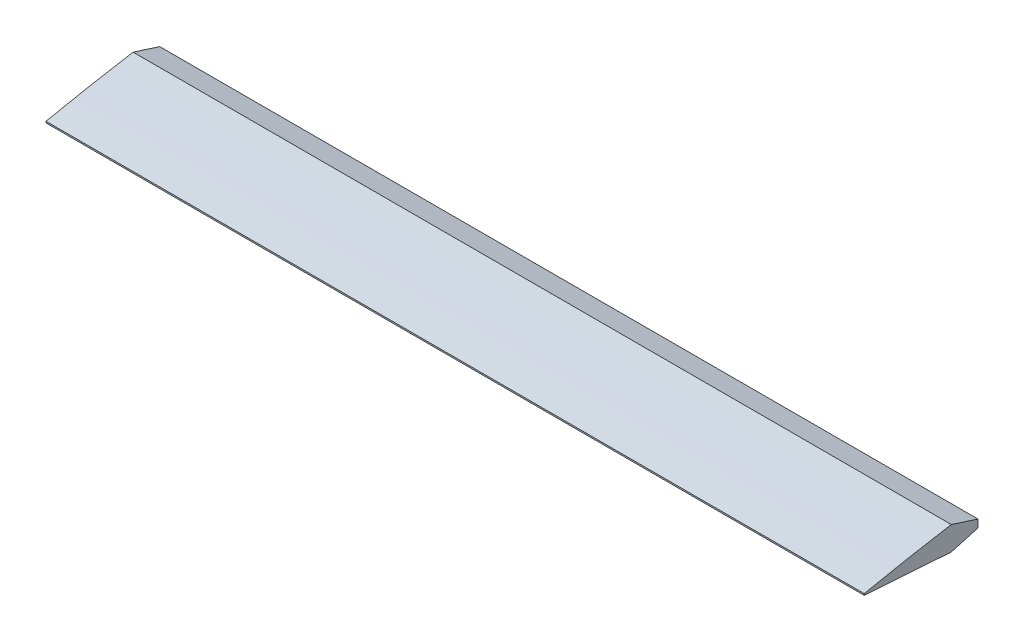
SolidWorks part; units mm, degrees
ref_plane "Front Plane" through (0, 0, 0) normal (0, 0, 1) x (1, 0, 0)
ref_plane "Top Plane" through (0, 0, 0) normal (0, 1, 0) x (1, 0, 0)
ref_plane "Right Plane" through (0, 0, 0) normal (1, 0, 0) x (0, 0, -1)
sketch "Sketch4" plane through (0, 0, 0) normal (0, 0, 1) x (1, 0, 0)
  line L0 (-30.3109, 17.5) -> (30.3109, 17.5)
  arc A1 (30.3109, 17.5) -> (-30.3109, 17.5) centre (0, 0) ccw
  dimension "D1" = 35
  dimension "D2" = 17.5
extrude "Exterior" add sketch "Sketch4" along normal blind 89 contours L0 A1
sketch "Sketch5" plane through (0, 0, 0) normal (0, 0, -1) x (-1, 0, 0)
  line L0 (30.3109, 17.5) -> (-30.3109, 17.5) construction
  line L1 (23.1247, 17.5) -> (-23.1247, 17.5)
  arc A0 (23.1247, 17.5) -> (-23.1247, 17.5) centre (0, 0) ccw
  dimension "D1" = 58
extrude "Boss-Extrude1" add sketch "Sketch5" along normal blind 15
curve "Curve3"
  spline degree 3 poles (0, 1.3, 1000) (0, 4.7133, 983.3426) (0, 11.531, 950.0715) (0, 24.0186, 883.4722) (0, 37.8548, 800.1781) (0, 52.175, 700.1592) (0, 64.1175, 600.1567) (0, 72.8619, 500.1109) (0, 78.7837, 400.0878) (0, 79.786, 316.6355) (0, 77.0249, 249.9395) (0, 72.979, 199.8766) (0, 66.5721, 149.7505) (0, 58.6825, 108.0331) (0, 49.7566, 74.7751) (0, 41.6416, 49.5609) (0, 32.1864, 28.1982) (0, 20.723, 9.771) (0, 0.8988, -6.2982) (0, -16.5264, 10.3934) (0, -24.4739, 28.476) (0, -30.5108, 49.7447) (0, -34.8393, 74.8759) (0, -38.5332, 108.2669) (0, -41.3764, 149.947) (0, -42.5163, 199.9941) (0, -42.3574, 250.0055) (0, -40.8857, 316.6783) (0, -38.2375, 400.0272) (0, -33.6287, 500.0334) (0, -27.6385, 600.0106) (0, -21.4122, 700.0048) (0, -15.1098, 800.0161) (0, -9.3053, 883.3314) (0, -4.8282, 950.0042) (0, -2.4761, 983.334) (0, -1.3, 1000) knots 0 0 0 0 0.025012 0.049959 0.099673 0.149206 0.198581 0.247805 0.296917 0.345953 0.370492 0.395091 0.419815 0.444799 0.45749 0.470406 0.483879 0.491264 0.503459 0.513609 0.520451 0.533235 0.545691 0.558032 0.582609 0.607135 0.631652 0.656174 0.705234 0.75432 0.803437 0.852566 0.901701 0.950849 0.975423 1 1 1 1
sketch "Sketch7" plane through (0, 0, 0) normal (1, 0, 0) x (0, 0, -1)
  line L0 (-89, 21.3887) -> (-89, 21.1573)
  line L1 (-89, 21.273) -> (0, 21.3903) construction
  line L2 (0, 21.3903) -> (-0.0573, 64.8516) construction
  line L7 (-89, 17.5) -> (0, 17.5) construction
  line L9 (0, 17.5) -> (0, 29) construction
  spline S1 degree 3 poles (-89, 21.3887) (-87.5176, 21.6924) (-84.5567, 22.2992) (-78.6297, 23.4105) (-71.2171, 24.6418) (-62.316, 25.9162) (-53.4164, 26.979) (-44.5129, 27.7573) (-35.6114, 28.2842) (-28.1847, 28.3735) (-22.2492, 28.1277) (-17.7939, 27.7677) (-13.3329, 27.1975) (-9.6203, 26.4954) (-6.6606, 25.701) (-4.4167, 24.9788) (-2.5155, 24.1374) (-0.8756, 23.1172) (0.5545, 21.353) (-0.931, 19.8022) (-2.5402, 19.095) (-4.433, 18.5577) (-6.6696, 18.1725) (-9.6412, 17.8438) (-13.3504, 17.5907) (-17.8043, 17.4893) (-22.255, 17.5034) (-28.1885, 17.6344) (-35.606, 17.8701) (-44.506, 18.2802) (-53.4034, 18.8133) (-62.3022, 19.3674) (-71.2026, 19.9283) (-78.6172, 20.4449) (-84.5507, 20.8433) (-87.5168, 21.0526) (-89, 21.1573) knots 0 0 0 0 0.025012 0.049959 0.099673 0.149206 0.198581 0.247805 0.296917 0.345953 0.370492 0.395091 0.419815 0.444799 0.45749 0.470406 0.483879 0.491264 0.503459 0.513609 0.520451 0.533235 0.545691 0.558032 0.582609 0.607135 0.631652 0.656174 0.705234 0.75432 0.803437 0.852566 0.901701 0.950849 0.975423 1 1 1 1
  dimension "D1" = 89
ref_plane "Plane1" through (80, 0, 0) normal (1, 0, 0) x (0, 0, -1)
ref_plane "Plane2" through (-80, 0, 0) normal (1, 0, 0) x (0, 0, -1)
sketch "Sketch8" plane through (80, 0, 0) normal (1, 0, 0) x (0, 0, -1)
  line L0 (-89, 21.3887) -> (-89, 21.1573)
  spline S0 degree 3 poles (-469.3669, 946.2185) (-209.3584, -26.81) (-147.9272, 10.417) (-78.6297, 23.4105) (-71.2171, 24.6418) (-62.316, 25.9162) (-53.4164, 26.979) (-44.5129, 27.7573) (-35.6114, 28.2842) (-28.1847, 28.3735) (-22.2492, 28.1277) (-17.7939, 27.7677) (-13.3329, 27.1975) (-9.6203, 26.4954) (-6.6606, 25.701) (-4.4167, 24.9788) (-2.5155, 24.1374) (-0.8756, 23.1172) (0.5545, 21.353) (-0.931, 19.8022) (-2.5402, 19.095) (-4.433, 18.5577) (-6.6696, 18.1725) (-9.6412, 17.8438) (-13.3504, 17.5907) (-17.8043, 17.4893) (-22.255, 17.5034) (-28.1885, 17.6344) (-35.606, 17.8701) (-44.506, 18.2802) (-53.4034, 18.8133) (-62.3022, 19.3674) (-71.2026, 19.9283) (-78.6172, 20.4449) (-191.4759, 28.0234) (-300.415, 49.2551) (-474.7288, -901.4445) knots -1.065698 -1.065698 -1.065698 -1.065698 0.025012 0.049959 0.099673 0.149206 0.198581 0.247805 0.296917 0.345953 0.370492 0.395091 0.419815 0.444799 0.45749 0.470406 0.483879 0.491264 0.503459 0.513609 0.520451 0.533235 0.545691 0.558032 0.582609 0.607135 0.631652 0.656174 0.705234 0.75432 0.803437 0.852566 0.901701 0.950849 0.975423 2.771414 2.771414 2.771414 2.771414 only from (-89, 21.3887) to (-89, 21.1573) construction
  spline S1 degree 3 poles (-89, 21.3887) (-87.5176, 21.6924) (-84.5567, 22.2992) (-78.6297, 23.4105) (-71.2171, 24.6418) (-62.316, 25.9162) (-53.4164, 26.979) (-44.5129, 27.7573) (-35.6114, 28.2842) (-28.1847, 28.3735) (-22.2492, 28.1277) (-17.7939, 27.7677) (-13.3329, 27.1975) (-9.6203, 26.4954) (-6.6606, 25.701) (-4.4167, 24.9788) (-2.5155, 24.1374) (-0.8756, 23.1172) (0.5545, 21.353) (-0.931, 19.8022) (-2.5402, 19.095) (-4.433, 18.5577) (-6.6696, 18.1725) (-9.6412, 17.8438) (-13.3504, 17.5907) (-17.8043, 17.4893) (-22.255, 17.5034) (-28.1885, 17.6344) (-35.606, 17.8701) (-44.506, 18.2802) (-53.4034, 18.8133) (-62.3022, 19.3674) (-71.2026, 19.9283) (-78.6172, 20.4449) (-84.5507, 20.8433) (-87.5168, 21.0526) (-89, 21.1573) knots 0 0 0 0 0.025012 0.049959 0.099673 0.149206 0.198581 0.247805 0.296917 0.345953 0.370492 0.395091 0.419815 0.444799 0.45749 0.470406 0.483879 0.491264 0.503459 0.513609 0.520451 0.533235 0.545691 0.558032 0.582609 0.607135 0.631652 0.656174 0.705234 0.75432 0.803437 0.852566 0.901701 0.950849 0.975423 1 1 1 1
sketch "Sketch9" plane through (-80, 0, 0) normal (1, 0, 0) x (0, 0, -1)
  line L0 (-89, 21.3887) -> (-89, 21.1573)
  spline S0 degree 3 poles (-469.3669, 946.2185) (-209.3584, -26.81) (-147.9272, 10.417) (-78.6297, 23.4105) (-71.2171, 24.6418) (-62.316, 25.9162) (-53.4164, 26.979) (-44.5129, 27.7573) (-35.6114, 28.2842) (-28.1847, 28.3735) (-22.2492, 28.1277) (-17.7939, 27.7677) (-13.3329, 27.1975) (-9.6203, 26.4954) (-6.6606, 25.701) (-4.4167, 24.9788) (-2.5155, 24.1374) (-0.8756, 23.1172) (0.5545, 21.353) (-0.931, 19.8022) (-2.5402, 19.095) (-4.433, 18.5577) (-6.6696, 18.1725) (-9.6412, 17.8438) (-13.3504, 17.5907) (-17.8043, 17.4893) (-22.255, 17.5034) (-28.1885, 17.6344) (-35.606, 17.8701) (-44.506, 18.2802) (-53.4034, 18.8133) (-62.3022, 19.3674) (-71.2026, 19.9283) (-78.6172, 20.4449) (-191.4759, 28.0234) (-300.415, 49.2551) (-474.7288, -901.4445) knots -1.065698 -1.065698 -1.065698 -1.065698 0.025012 0.049959 0.099673 0.149206 0.198581 0.247805 0.296917 0.345953 0.370492 0.395091 0.419815 0.444799 0.45749 0.470406 0.483879 0.491264 0.503459 0.513609 0.520451 0.533235 0.545691 0.558032 0.582609 0.607135 0.631652 0.656174 0.705234 0.75432 0.803437 0.852566 0.901701 0.950849 0.975423 2.771414 2.771414 2.771414 2.771414 only from (-89, 21.3887) to (-89, 21.1573) construction
  spline S1 degree 3 poles (-89, 21.3887) (-87.5176, 21.6924) (-84.5567, 22.2992) (-78.6297, 23.4105) (-71.2171, 24.6418) (-62.316, 25.9162) (-53.4164, 26.979) (-44.5129, 27.7573) (-35.6114, 28.2842) (-28.1847, 28.3735) (-22.2492, 28.1277) (-17.7939, 27.7677) (-13.3329, 27.1975) (-9.6203, 26.4954) (-6.6606, 25.701) (-4.4167, 24.9788) (-2.5155, 24.1374) (-0.8756, 23.1172) (0.5545, 21.353) (-0.931, 19.8022) (-2.5402, 19.095) (-4.433, 18.5577) (-6.6696, 18.1725) (-9.6412, 17.8438) (-13.3504, 17.5907) (-17.8043, 17.4893) (-22.255, 17.5034) (-28.1885, 17.6344) (-35.606, 17.8701) (-44.506, 18.2802) (-53.4034, 18.8133) (-62.3022, 19.3674) (-71.2026, 19.9283) (-78.6172, 20.4449) (-84.5507, 20.8433) (-87.5168, 21.0526) (-89, 21.1573) knots 0 0 0 0 0.025012 0.049959 0.099673 0.149206 0.198581 0.247805 0.296917 0.345953 0.370492 0.395091 0.419815 0.444799 0.45749 0.470406 0.483879 0.491264 0.503459 0.513609 0.520451 0.533235 0.545691 0.558032 0.582609 0.607135 0.631652 0.656174 0.705234 0.75432 0.803437 0.852566 0.901701 0.950849 0.975423 1 1 1 1
loft "Loft9" add profiles "Sketch8", "Sketch9"
sketch "Sketch12" plane through (80, 0, 0) normal (1, 0, 0) x (0, 0, -1)
  line L0 (-89, 21.3887) -> (-89, 21.1573) construction
  line L1 (-89, 21.3887) -> (-89, 21.1573)
  line L2 (-89, 21.3887) -> (-97.2409, 26.9065)
  line L3 (-97.2409, 26.9065) -> (-90.2923, 42.7722)
  line L4 (-90.2923, 42.7722) -> (-30.1138, 44.0233)
  line L5 (-30.1138, 44.0233) -> (6.4186, 38.5184)
  line L6 (6.4186, 38.5184) -> (-0.0099, 28.9175)
  line L7 (0, 21.3903) -> (-0.0573, 64.8516) construction
  line L8 (-0.0099, 28.9175) -> (-30.6202, 28.3197)
  spline S0 degree 3 poles (-713.3875, 1915.884) (-239.966, -47.1163) (-164.6221, 7.2867) (-78.6297, 23.4105) (-71.2171, 24.6418) (-62.316, 25.9162) (-53.4164, 26.979) (-44.5129, 27.7573) (-35.6114, 28.2842) (-28.1847, 28.3735) (-22.2492, 28.1277) (-17.7939, 27.7677) (-13.3329, 27.1975) (-9.6203, 26.4954) (-6.6606, 25.701) (-4.4167, 24.9788) (-2.5155, 24.1374) (-0.8756, 23.1172) (0.5545, 21.353) (-0.931, 19.8022) (-2.5402, 19.095) (-4.433, 18.5577) (-6.6696, 18.1725) (-9.6412, 17.8438) (-13.3504, 17.5907) (-17.8043, 17.4893) (-22.255, 17.5034) (-28.1885, 17.6344) (-35.606, 17.8701) (-44.506, 18.2802) (-53.4034, 18.8133) (-62.3022, 19.3674) (-71.2026, 19.9283) (-78.6172, 20.4449) (-220.4152, 29.9667) (-357.7257, 61.3982) (-629.9057, -1889.2617) knots -1.346455 -1.346455 -1.346455 -1.346455 0.025012 0.049959 0.099673 0.149206 0.198581 0.247805 0.296917 0.345953 0.370492 0.395091 0.419815 0.444799 0.45749 0.470406 0.483879 0.491264 0.503459 0.513609 0.520451 0.533235 0.545691 0.558032 0.582609 0.607135 0.631652 0.656174 0.705234 0.75432 0.803437 0.852566 0.901701 0.950849 0.975423 3.250848 3.250848 3.250848 3.250848 only from (-89, 21.3887) to (-89, 21.1573) construction
  spline S1 degree 3 poles (-89, 21.3887) (-87.5176, 21.6924) (-84.5567, 22.2992) (-78.6297, 23.4105) (-71.2171, 24.6418) (-62.316, 25.9162) (-53.4164, 26.979) (-44.5129, 27.7573) (-36.9147, 28.2071) (-32.2817, 28.3107) (-30.6202, 28.3197) knots 0 0 0 0 0.025012 0.049959 0.099673 0.149206 0.198581 0.247805 0.296917 0.324377 0.324377 0.324377 0.324377
  spline S2 degree 3 poles (-89, 21.3887) (-87.5176, 21.6924) (-84.5567, 22.2992) (-78.6297, 23.4105) (-71.2171, 24.6418) (-62.316, 25.9162) (-53.4164, 26.979) (-44.5129, 27.7573) (-36.9147, 28.2071) (-32.2817, 28.3107) (-30.6202, 28.3197) knots 0 0 0 0 0.025012 0.049959 0.099673 0.149206 0.198581 0.247805 0.296917 0.324377 0.324377 0.324377 0.324377
extrude "Cut-Extrude1" cut sketch "Sketch12" against normal through all
ref_plane "Plane3" through (0, 30, 0) normal (0, 1, 0) x (1, 0, 0)
sketch "Sketch17" plane through (-80, 0, 0) normal (-1, 0, 0) x (0, 0, 1)
  line L0 (89, 21.3887) -> (89, 21.1573) construction
  line L1 (89, 21.3887) -> (89, 21.1573)
  spline S0 degree 3 poles (713.3875, 1915.884) (239.966, -47.1163) (164.6221, 7.2867) (78.6297, 23.4105) (71.2171, 24.6418) (62.316, 25.9162) (53.4164, 26.979) (44.5129, 27.7573) (35.6114, 28.2842) (28.1847, 28.3735) (22.2492, 28.1277) (17.7939, 27.7677) (13.3329, 27.1975) (9.6203, 26.4954) (6.6606, 25.701) (4.4167, 24.9788) (2.5155, 24.1374) (0.8756, 23.1172) (-0.5545, 21.353) (0.931, 19.8022) (2.5402, 19.095) (4.433, 18.5577) (6.6696, 18.1725) (9.6412, 17.8438) (13.3504, 17.5907) (17.8043, 17.4893) (22.255, 17.5034) (28.1885, 17.6344) (35.606, 17.8701) (44.506, 18.2802) (53.4034, 18.8133) (62.3022, 19.3674) (71.2026, 19.9283) (78.6172, 20.4449) (220.4152, 29.9667) (357.7257, 61.3982) (629.9057, -1889.2617) knots -1.346455 -1.346455 -1.346455 -1.346455 0.025012 0.049959 0.099673 0.149206 0.198581 0.247805 0.296917 0.345953 0.370492 0.395091 0.419815 0.444799 0.45749 0.470406 0.483879 0.491264 0.503459 0.513609 0.520451 0.533235 0.545691 0.558032 0.582609 0.607135 0.631652 0.656174 0.705234 0.75432 0.803437 0.852566 0.901701 0.950849 0.975423 3.250848 3.250848 3.250848 3.250848 only from (89, 21.3887) to (89, 21.1573) construction
  spline S1 degree 3 poles (89, 21.3887) (87.5176, 21.6924) (84.5567, 22.2992) (78.6297, 23.4105) (71.2171, 24.6418) (62.316, 25.9162) (53.4164, 26.979) (44.5129, 27.7573) (35.6114, 28.2842) (28.1847, 28.3735) (22.2492, 28.1277) (17.7939, 27.7677) (13.3329, 27.1975) (9.6203, 26.4954) (6.6606, 25.701) (4.4167, 24.9788) (2.5155, 24.1374) (0.8756, 23.1172) (-0.5545, 21.353) (0.931, 19.8022) (2.5402, 19.095) (4.433, 18.5577) (6.6696, 18.1725) (9.6412, 17.8438) (13.3504, 17.5907) (17.8043, 17.4893) (22.255, 17.5034) (28.1885, 17.6344) (35.606, 17.8701) (44.506, 18.2802) (53.4034, 18.8133) (62.3022, 19.3674) (71.2026, 19.9283) (78.6172, 20.4449) (84.5507, 20.8433) (87.5168, 21.0526) (89, 21.1573) knots 0 0 0 0 0.025012 0.049959 0.099673 0.149206 0.198581 0.247805 0.296917 0.345953 0.370492 0.395091 0.419815 0.444799 0.45749 0.470406 0.483879 0.491264 0.503459 0.513609 0.520451 0.533235 0.545691 0.558032 0.582609 0.607135 0.631652 0.656174 0.705234 0.75432 0.803437 0.852566 0.901701 0.950849 0.975423 1 1 1 1
extrude "Boss-Extrude2" add sketch "Sketch17" along normal blind 170
ref_plane "Plane5" through (-165, 0, 0) normal (1, 0, 0) x (0, 0, -1)
ref_plane "Plane6" through (-80, 0, 0) normal (1, 0, 0) x (0, 0, -1)
sketch "Sketch18" plane through (-80, 0, 0) normal (1, 0, 0) x (0, 0, -1)
  line L0 (-99.867, 5.7154) -> (-104.3901, 63.3258)
  line L1 (-104.3901, 63.3258) -> (31.8989, 60.8261)
  line L2 (31.8989, 60.8261) -> (39.2788, -3.2119)
  line L3 (39.2788, -3.2119) -> (-99.867, 5.7154)
extrude "Cut-Extrude6" cut sketch "Sketch18" along normal through all
sketch "Sketch13" plane through (-80, 0, 0) normal (-1, 0, 0) x (0, 0, 1)
  line L0 (20, 17.5005) -> (20, 27.9379) construction
  circle A0 centre (20, 22.7192) radius 3.25
  spline S0 degree 3 poles (89, 21.3887) (87.5176, 21.6924) (84.5567, 22.2992) (78.6297, 23.4105) (71.2171, 24.6418) (62.316, 25.9162) (53.4164, 26.979) (44.5129, 27.7573) (35.6114, 28.2842) (28.1847, 28.3735) (22.2492, 28.1277) (17.7939, 27.7677) (13.3329, 27.1975) (9.6203, 26.4954) (6.6606, 25.701) (4.4167, 24.9788) (2.5155, 24.1374) (0.8756, 23.1172) (-0.5545, 21.353) (0.931, 19.8022) (2.5402, 19.095) (4.433, 18.5577) (6.6696, 18.1725) (9.6412, 17.8438) (13.3504, 17.5907) (17.8043, 17.4893) (22.255, 17.5034) (28.1885, 17.6344) (35.606, 17.8701) (44.506, 18.2802) (53.4034, 18.8133) (62.3022, 19.3674) (71.2026, 19.9283) (78.6172, 20.4449) (84.5507, 20.8433) (87.5168, 21.0526) (89, 21.1573) knots 0 0 0 0 0.025012 0.049959 0.099673 0.149206 0.198581 0.247805 0.296917 0.345953 0.370492 0.395091 0.419815 0.444799 0.45749 0.470406 0.483879 0.491264 0.503459 0.513609 0.520451 0.533235 0.545691 0.558032 0.582609 0.607135 0.631652 0.656174 0.705234 0.75432 0.803437 0.852566 0.901701 0.950849 0.975423 1 1 1 1 construction
  point P8 (20, 22.7192)
  dimension "D1" = 6.5
  dimension "D2" = 20
extrude "Cut-Extrude2" cut sketch "Sketch13" against normal through all and the other way through all
sketch "Sketch19" plane through (0, 0, 0) normal (0, 1, 0) x (1, 0, 0)
  line L0 (-183.5, -62.5) -> (-183.5, -26.5)
  line L1 (-183.5, -26.5) -> (-146.5, -26.5)
  line L2 (-146.5, -26.5) -> (-146.5, -62.5)
  line L3 (-146.5, -62.5) -> (-183.5, -62.5)
  line L4 (-165, -9.0116) -> (-165, 9.0116) construction
  line L6 (-80, 0) -> (-250, 0) construction
  point P6 (-165, -62.5)
  point P7 (-183.5, -44.5)
  dimension "D1" = 36
  dimension "D2" = 37
  dimension "D3" = 44.5
extrude "Cut-Extrude7" cut sketch "Sketch19" along normal blind 23
sketch "Sketch20" plane through (0, 30, 0) normal (0, 1, 0) x (1, 0, 0)
  line L0 (-229, -89) -> (-229, -71.2)
  line L1 (-229, -71.2) -> (-101, -71.2)
  line L2 (-101, -71.2) -> (-101, -89)
  line L3 (-250, -89) -> (-80, -89) construction
  line L5 (-250, 0) -> (-250, -89) construction
  line L6 (-80, -89) -> (-80, 0) construction
  line L7 (-229, -89) -> (-250, -89)
  line L8 (-250, -89) -> (-250, 0)
  line L9 (-250, 0) -> (-80, 0)
  line L10 (-80, 0) -> (-80, -89)
  line L11 (-80, -89) -> (-101, -89)
  dimension "D1" = 21
  dimension "D2" = 21
extrude "Cut-Extrude8" cut sketch "Sketch20" against normal through all
sketch "Sketch21" plane through (-229, 0, 0) normal (-1, 0, 0) x (0, 0, 1)
  line L0 (71.2, 21.3931) -> (75.3752, 20.22)
  line L1 (71.2, 19.938) -> (71.2, 24.6104) construction
  line L2 (71.2, 22.5975) -> (75.3752, 23.9416)
  line L7 (75.3752, 20.22) -> (73.9843, 18.5521)
  line L8 (73.9843, 18.5521) -> (70.1577, 19.386)
  line L9 (70.1577, 19.386) -> (71.2, 21.3931)
  line L10 (71.2, 22.5975) -> (69.8099, 24.5575)
  line L11 (69.8099, 24.5575) -> (72.8492, 25.7476)
  line L12 (72.8492, 25.7476) -> (75.3752, 23.9416)
  spline S0 degree 3 poles (89, 21.1573) (87.5168, 21.0526) (84.5507, 20.8433) (78.6168, 20.4448) (74.1672, 20.1348) (71.2, 19.938) knots 0.901694 0.901694 0.901694 0.901694 0.926272 0.950845 1 1 1 1 construction
  spline S1 degree 3 poles (71.2, 24.6104) (74.1727, 24.1509) (78.6293, 23.4106) (84.5567, 22.2992) (87.5176, 21.6924) (89, 21.3887) knots 0 0 0 0 0.04972 0.074667 0.09968 0.09968 0.09968 0.09968 construction
extrude "Cut-Extrude9" cut sketch "Sketch21" against normal through all
equation "\"fuse_diam\"= 0.07"
equation "\"fuse_rad\"= 0.035"
equation "\"battery_length\"= 0.076"
equation "\"battery_width\"= 0.034"
equation "\"battery_height\"= 0.051"
equation "\"bat_bay_length\"= 0.096"
equation "\"shell\"= 0.002"
equation "\"D1@Exterior\"=\"chord_length\""
equation "\"wing_shelf\"= 0.0175"
equation "\"chord_length\"= 0.089"
equation "\"tail_length\"= 0.26532000000000006"
equation "\"tail_diam\"= 0.035"
equation "\"connector\"= 0.06633000000000001"
equation "\"D2@Sketch4\"=\"wing_shelf\""
equation "\"D1@Sketch4\"=\"fuse_rad\""
equation "\"D1@Sketch5\"=\"fuse_diam\"-0.012"
equation "\"D1@Sketch7\"=\"chord_length\""
equation "\"D3@Sketch19\"=\"chord_length\"/2"
